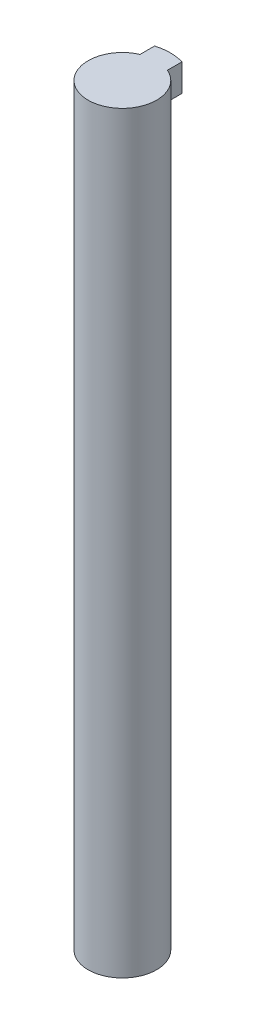
SolidWorks part; units mm, degrees
ref_plane "Front Plane" through (0, 0, 0) normal (0, 0, 1) x (1, 0, 0)
ref_plane "Top Plane" through (0, 0, 0) normal (0, 1, 0) x (1, 0, 0)
ref_plane "Right Plane" through (0, 0, 0) normal (1, 0, 0) x (0, 0, -1)
sketch "Sketch1" plane through (0, 0, 0) normal (0, 1, 0) x (1, 0, 0)
  circle A0 centre (0, 0) radius 3.175
  dimension "D1" = 6.35
extrude "Boss-Extrude1" add sketch "Sketch1" along normal blind 69.85 contours A0
sketch "Sketch2" plane through (0, 69.85, 0) normal (0, 1, 0) x (1, 0, 0)
  line L0 (0, 0) -> (0, 3.175) construction
  line L1 (0, 3.175) -> (0, 4.445) construction
  line L3 (1.27, 4.2597) -> (1.27, 2.9099)
  line L4 (-1.27, 4.2597) -> (-1.27, 2.9099)
  circle A0 centre (0, 0) radius 3.175 construction
  arc A1 (1.27, 4.2597) -> (-1.27, 4.2597) centre (0, 0) ccw
  arc A2 (1.27, 2.9099) -> (-1.27, 2.9099) centre (0, 0) ccw
  dimension "D2" = 2.54
  dimension "D1" = 1.27
extrude "Boss-Extrude2" add sketch "Sketch2" against normal blind 2.54
